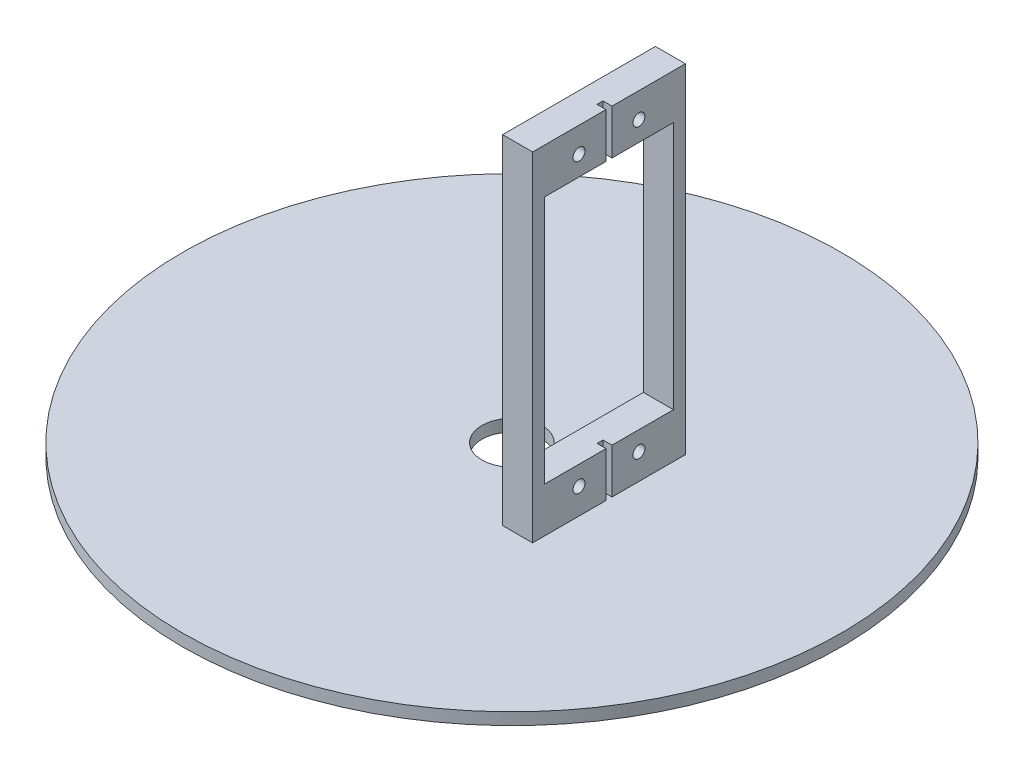
SolidWorks part; units mm, degrees
ref_plane "Front Plane" through (0, 0, 0) normal (0, 0, 1) x (1, 0, 0)
ref_plane "Top Plane" through (0, 0, 0) normal (0, 1, 0) x (1, 0, 0)
ref_plane "Right Plane" through (0, 0, 0) normal (1, 0, 0) x (0, 0, -1)
sketch "Sketch1" plane through (0, 0, 0) normal (0, 1, 0) x (1, 0, 0)
  circle A0 centre (0, 0) radius 55
  dimension "D1" = 110
extrude "Boss-Extrude1" add sketch "Sketch1" along normal blind 2
sketch "Sketch2" plane through (0, 2, 0) normal (0, 1, 0) x (1, 0, 0)
  circle A0 centre (0, 0) radius 5
extrude "Cut-Extrude1" cut sketch "Sketch2" against normal through all
ref_plane "Plane2" through (16.2, 0, 0) normal (1, 0, 0) x (0, 0, -1)
sketch "Sketch4" plane through (16.2, 0, 0) normal (1, 0, 0) x (0, 0, -1)
  line L0 (-12.75, 2) -> (-12.75, 58.5)
  line L1 (55, 2) -> (-55, 2) construction
  line L2 (-12.75, 58.5) -> (12.75, 58.5)
  line L3 (12.75, 58.5) -> (12.75, 2)
  line L4 (12.75, 2) -> (-12.75, 2)
  line L5 (-10.75, 51) -> (10.75, 51)
  line L6 (10.75, 51) -> (10.75, 9.5)
  line L7 (10.75, 9.5) -> (-10.75, 9.5)
  line L8 (-10.75, 9.5) -> (-10.75, 51)
  point P8 (0, 2)
  point P11 (0, 9.5)
  dimension "D1" = 21.5
  dimension "D2" = 25.5
  dimension "D3" = 0
  dimension "D4" = 0
  dimension "D5" = 7.5
  dimension "D6" = 41.5
  dimension "D7" = 7.5
extrude "Boss-Extrude2" add sketch "Sketch4" against normal blind 5
sketch "Sketch5" plane through (16.2, 0, 0) normal (1, 0, 0) x (0, 0, -1)
  line L0 (55, 2) -> (-55, 2) construction
  line L1 (0, 32.175) -> (0, -32.175) construction
  circle A0 centre (-5, 54.3) radius 1
  circle A1 centre (-5, 6.3) radius 1
  circle A2 centre (5, 6.3) radius 1
  circle A3 centre (5, 54.3) radius 1
  dimension "D1" = 2
  dimension "D2" = 2
  dimension "D3" = 48
  dimension "D4" = 4.3
  dimension "D5" = 5
  dimension "D6" = 5
extrude "Cut-Extrude2" cut sketch "Sketch5" against normal through all
sketch "Sketch6" plane through (16.2, 0, 0) normal (1, 0, 0) x (0, 0, -1)
  line L0 (0, 58.5) -> (0, 2) construction
  line L1 (12.75, 58.5) -> (-12.75, 58.5) construction
  line L2 (55, 2) -> (-55, 2) construction
  line L3 (-0.5, 58.5) -> (-0.5, 2)
  line L4 (0.5, 58.5) -> (0.5, 2)
  line L5 (-0.5, 58.5) -> (0.5, 58.5)
  line L6 (-0.5, 2) -> (0.5, 2)
  dimension "D1" = 0.5
  dimension "D2" = 0.5
extrude "Cut-Extrude3" cut sketch "Sketch6" against normal blind 1.5
